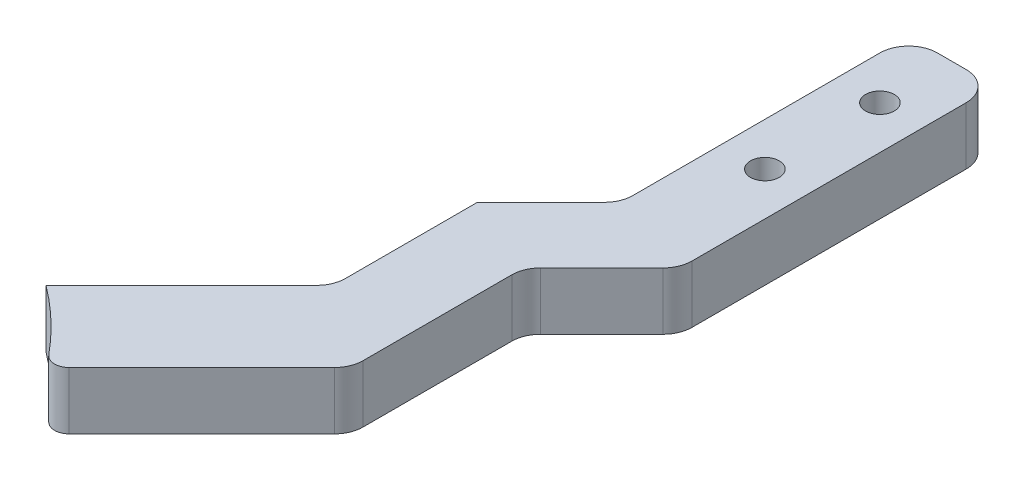
SolidWorks part; units mm, degrees
material "Thornel Mat VMA"
ref_plane "前视基准面" through (0, 0, 0) normal (0, 0, 1) x (1, 0, 0)
ref_plane "上视基准面" through (0, 0, 0) normal (0, 1, 0) x (1, 0, 0)
ref_plane "右视基准面" through (0, 0, 0) normal (1, 0, 0) x (0, 0, -1)
other "Configuration Table"
sketch "草图1" plane through (0, 0, 0) normal (0, 1, 0) x (1, 0, 0)
  line L0 (0, 0) -> (0, 40.389) construction
  line L1 (0, 0) -> (49.8304, 0) construction
  line L2 (0, 35) -> (25, 35) construction
  line L3 (25, 35) -> (25, 30) construction
  line L4 (15, 20) -> (25, 30)
  line L5 (25, 30) -> (15, 20) construction
  line L6 (25, -30) -> (15, -20) construction
  line L7 (25, 30) -> (25, 40)
  line L8 (25, -35) -> (25, -30) construction
  line L9 (0, -35) -> (25, -35) construction
  line L10 (0, 35) -> (0, -35) construction
  line L12 (30.5635, 25.664) -> (30.5635, 37.664)
  line L13 (30.5635, 25.664) -> (19.9569, 15.0574)
  line L14 (25, 40) -> (30, 45)
  line L17 (30.5635, 37.664) -> (36, 43.1005)
  line L18 (30, 45) -> (30, 65)
  line L19 (30, 65) -> (36, 65)
  line L20 (36, 65) -> (36, 43.1005)
  line L21 (33, 65) -> (33, 39.979) construction
  arc A0 (15, -20) -> (15, 20) centre (0, 0) ccw construction
  arc A1 (15, 20) -> (19.9569, 15.0574) centre (0, 0) cw
  circle A4 centre (33, 60) radius 1
  circle A5 centre (33, 52) radius 1
  dimension "D3" = 50
  dimension "D11" = 0
  dimension "D12" = 20
  dimension "D13" = 2
  dimension "D14" = 2
  dimension "D15" = 8
  dimension "D16" = 5
  dimension "D1" = 5
  dimension "D2" = 25
  dimension "D4" = 35
  dimension "D5" = 45
  dimension "D6" = 7
  dimension "D7" = 135
  dimension "D8" = 10
  dimension "D9" = 5
  dimension "D10" = 6
  dimension "D18" = 15
  dimension "D19" = 12
extrude "凸台-拉伸1" add sketch "草图1" along normal blind 4
fillet "圆角1" radius 2 7 edges at (25, 2, -30) (30.5635, 2, -25.664) (30.5635, 2, -37.664) (30, 2, -45) (36, 2, -43.1005) (36, 2, -65) (30, 2, -65)
fillet "圆角2" radius 1 1 edges at (19.9569, 2, -15.0574)
